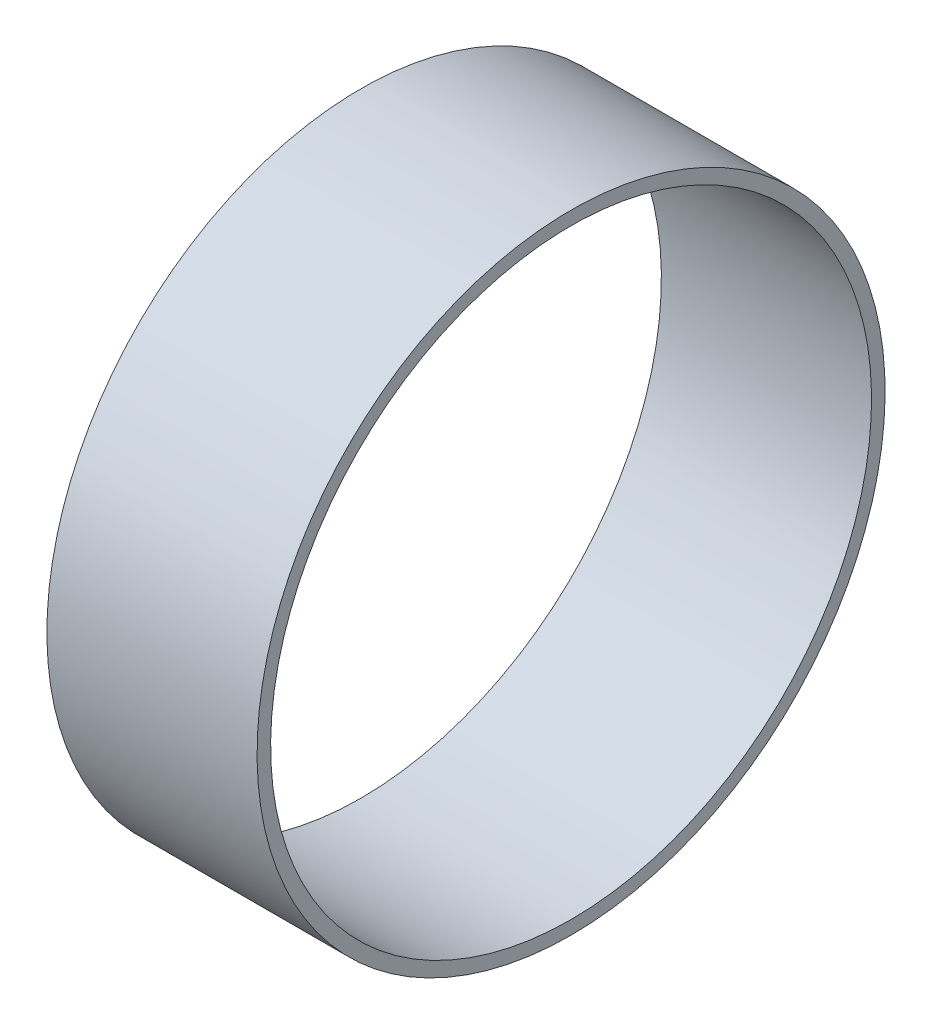
SolidWorks part; units mm, degrees
ref_plane "Plan1" through (0, 0, 0) normal (0, 0, 1) x (1, 0, 0)
ref_plane "Plan2" through (0, 0, 0) normal (0, 1, 0) x (1, 0, 0)
ref_plane "Plan3" through (0, 0, 0) normal (1, 0, 0) x (0, 0, -1)
sketch "Esquisse1" plane through (0, 0, 0) normal (0, 0, 1) x (1, 0, 0)
  line L0 (29.75, 23.16) -> (45.25, 23.16)
  line L1 (44.75, 0) -> (45.25, 0) construction
  line L2 (45.25, -24.7) -> (45.25, 24.7) construction
  line L3 (29.75, 24.7) -> (29.75, -24.7) construction
  line L4 (0, 0) -> (38.7669, 0) construction
  line L5 (30.25, 0) -> (29.75, 0) construction
  dimension "D1" = 23.16
revolve "Base-Révol.-Mince" add sketch "Esquisse1" angle 360 about L4
